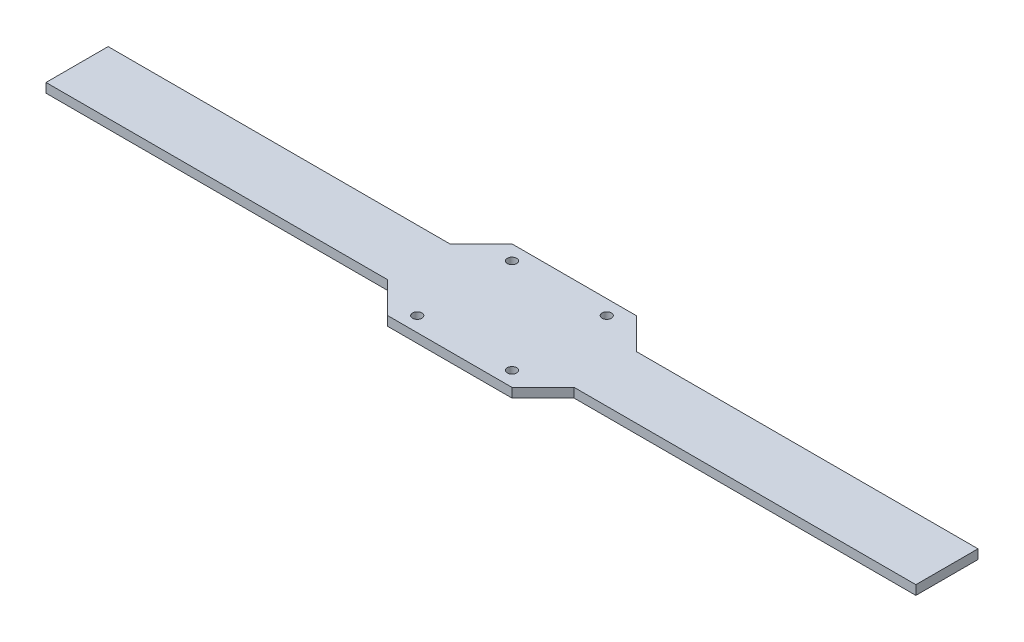
SolidWorks part; units mm, degrees
ref_plane "Front Plane" through (0, 0, 0) normal (0, 0, 1) x (1, 0, 0)
ref_plane "Top Plane" through (0, 0, 0) normal (0, 1, 0) x (1, 0, 0)
ref_plane "Right Plane" through (0, 0, 0) normal (1, 0, 0) x (0, 0, -1)
sketch "Sketch1" plane through (0, 0, 0) normal (0, 1, 0) x (1, 0, 0)
  line L0 (-140, 0) -> (140, 0) construction
  line L1 (15.25, 15.25) -> (-15.25, 15.25) construction
  line L2 (15.25, 15.25) -> (15.25, -15.25) construction
  line L3 (15.25, -15.25) -> (-15.25, -15.25) construction
  line L4 (-15.25, 15.25) -> (-15.25, -15.25) construction
  line L5 (15.25, 15.25) -> (-15.25, -15.25) construction
  line L6 (15.25, -15.25) -> (-15.25, 15.25) construction
  line L7 (140, 20) -> (-140, 20)
  line L8 (140, 20) -> (140, -20)
  line L9 (140, -20) -> (-140, -20)
  line L10 (-140, 20) -> (-140, -20)
  line L11 (140, 20) -> (-140, -20) construction
  line L12 (140, -20) -> (-140, 20) construction
  line L13 (-140, 10) -> (-30, 10)
  line L14 (-30, 10) -> (-20, 20)
  line L15 (-30, -10) -> (-20, -20)
  line L16 (-140, -10) -> (-30, -10)
  line L17 (0, 20) -> (0, -20) construction
  line L18 (30, -10) -> (20, -20)
  line L19 (140, -10) -> (30, -10)
  line L20 (30, 10) -> (20, 20)
  line L21 (140, 10) -> (30, 10)
  circle A0 centre (-15.25, 15.25) radius 1.5
  circle A1 centre (15.25, 15.25) radius 1.5
  circle A2 centre (15.25, -15.25) radius 1.5
  circle A3 centre (-15.25, -15.25) radius 1.5
  point P0 (0, 0)
  point P10 (0, 0)
  dimension "D2" = 3
  dimension "D1" = 30.5
  dimension "D3" = 280
  dimension "D4" = 40
  dimension "D5" = 10
  dimension "D6" = 10
  dimension "D7" = 120
extrude "Boss-Extrude1" add sketch "Sketch1" along normal mid plane 3 contours L8 L21 L20 L7 L14 L13 L10 L16 L15 L9 L18 L19 A3 A2 A1 A0
sketch "Sketch2" plane through (0, 0, 0) normal (1, 0, 0) x (0, -1, 0)
  line L0 (-250, 0) -> (250, 0) construction
  dimension "D1" = 500
